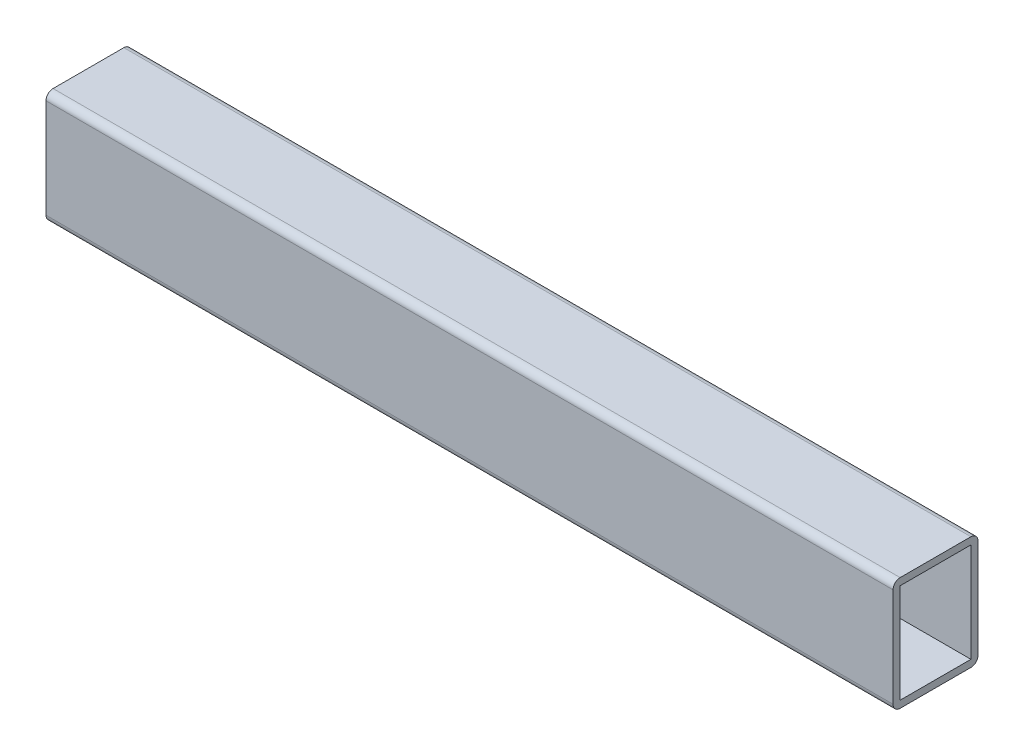
SolidWorks part; units mm, degrees
ref_plane "Front Plane" through (0, 0, 0) normal (0, 0, 1) x (1, 0, 0)
ref_plane "Top Plane" through (0, 0, 0) normal (0, 1, 0) x (1, 0, 0)
ref_plane "Right Plane" through (0, 0, 0) normal (1, 0, 0) x (0, 0, -1)
sketch "Sketch1" plane through (0, 0, 0) normal (1, 0, 0) x (0, 0, -1)
  line L0 (-19.05, 0) -> (19.05, 0) construction
  line L1 (-15.875, 25.4) -> (15.875, 25.4)
  line L2 (-19.05, 22.225) -> (-19.05, -22.225)
  line L3 (-15.875, -25.4) -> (15.875, -25.4)
  line L4 (19.05, 22.225) -> (19.05, -22.225)
  line L5 (0, 25.4) -> (0, -25.4) construction
  line L6 (-15.875, 22.225) -> (15.875, 22.225)
  line L7 (-15.875, 22.225) -> (-15.875, -22.225)
  line L8 (-15.875, -22.225) -> (15.875, -22.225)
  line L9 (15.875, 22.225) -> (15.875, -22.225)
  arc A0 (-15.875, 25.4) -> (-19.05, 22.225) centre (-15.875, 22.225) ccw
  arc A1 (19.05, 22.225) -> (15.875, 25.4) centre (15.875, 22.225) ccw
  arc A2 (-15.875, -25.4) -> (-19.05, -22.225) centre (-15.875, -22.225) cw
  arc A3 (15.875, -25.4) -> (19.05, -22.225) centre (15.875, -22.225) ccw
  point P10 (-19.05, 25.4)
  point P13 (19.05, 25.4)
  point P18 (19.05, -25.4)
  dimension "D3" = 3.175
  dimension "D1" = 50.8
  dimension "D2" = 38.1
  dimension "D4" = 3.175
  dimension "D5" = 3.175
extrude "Extrude1" add sketch "Sketch1" along normal blind 380
sketch "Mounting Holes" plane through (0, 0, 0) normal (0, -1, 0) x (1, 0, 0)
  line L0 (0, 0) -> (380, 0) construction
  line L1 (8.75, 10.05) -> (28.85, 10.05) construction
  line L2 (8.75, 10.05) -> (8.75, -10.05) construction
  line L3 (8.75, -10.05) -> (28.85, -10.05) construction
  line L4 (28.85, 10.05) -> (28.85, -10.05) construction
  line L5 (380, 15.875) -> (380, -15.875) construction
  line L6 (190, 19.05) -> (190, -19.05) construction
  line L7 (380, 19.05) -> (0, 19.05) construction
  line L8 (380, -19.05) -> (0, -19.05) construction
  line L9 (0, 15.875) -> (0, -15.875) construction
  line L10 (351.15, 10.05) -> (351.15, -10.05) construction
  line L11 (371.25, -10.05) -> (351.15, -10.05) construction
  line L12 (371.25, 10.05) -> (371.25, -10.05) construction
  line L13 (371.25, 10.05) -> (351.15, 10.05) construction
  circle A0 centre (8.75, 10.05) radius 2.1082
  circle A1 centre (28.85, 10.05) radius 2.1082
  circle A2 centre (28.85, -10.05) radius 2.1082
  circle A3 centre (8.75, -10.05) radius 2.1082
  circle A4 centre (351.15, 10.05) radius 2.1082
  circle A5 centre (371.25, 10.05) radius 2.1082
  circle A6 centre (371.25, -10.05) radius 2.1082
  circle A7 centre (351.15, -10.05) radius 2.1082
  dimension "D3" = 4.2164
  dimension "D1" = 9
  dimension "D2" = 8.75
sketch "Track" plane through (0, 0, 0) normal (0, 0, 1) x (1, 0, 0)
  line L0 (0, -11.96) -> (380, -11.96) construction
  line L1 (0, 22.225) -> (0, -22.225) construction
  line L2 (380, 22.225) -> (380, -22.225) construction
  line L3 (380, -25.4) -> (0, -25.4) construction
  line L4 (54, -3.96) -> (326, -3.96)
  line L5 (54, -3.96) -> (54, -19.96) construction
  line L6 (54, -19.96) -> (326, -19.96)
  line L7 (326, -3.96) -> (326, -19.96) construction
  arc A0 (54, -19.96) -> (54, -3.96) centre (54, -11.96) cw
  arc A1 (326, -19.96) -> (326, -3.96) centre (326, -11.96) ccw
  dimension "D1" = 16
  dimension "D2" = 54
  dimension "D3" = 326
  dimension "D4" = 13.44
sketch "Motor Mounts" plane through (0, 0, 0) normal (0, 0, 1) x (1, 0, 0)
  line L0 (0, -6.16) -> (380, -6.16) construction
  line L1 (0, 22.225) -> (0, -22.225) construction
  line L2 (380, 22.225) -> (380, -22.225) construction
  line L3 (380, -25.4) -> (0, -25.4) construction
  circle A0 centre (25, -6.16) radius 11.3109
  circle A1 centre (3.08, -6.16) radius 0.889
  circle A2 centre (25, 15.76) radius 0.889
  circle A3 centre (46.92, -6.16) radius 0.889
  circle A4 centre (25, -28.08) radius 0.889
  dimension "D2" = 22.6219
  dimension "D4" = 1.778
  dimension "D1" = 19.24
  dimension "D3" = 25
  dimension "D5" = 3.08
sketch "Access Port" plane through (0, 0, 0) normal (0, 0, 1) x (1, 0, 0)
  line L0 (253, 11.4) -> (253, -11.4)
  line L1 (380, 25.4) -> (0, 25.4) construction
  line L2 (380, -25.4) -> (0, -25.4) construction
  line L3 (380, 22.225) -> (380, -22.225) construction
  line L5 (261, -19.4) -> (350, -19.4)
  line L6 (358, 11.4) -> (358, -11.4)
  line L7 (261, 19.4) -> (350, 19.4)
  arc A0 (261, 19.4) -> (253, 11.4) centre (261, 11.4) ccw
  arc A1 (358, 11.4) -> (350, 19.4) centre (350, 11.4) ccw
  arc A2 (350, -19.4) -> (358, -11.4) centre (350, -11.4) ccw
  arc A3 (253, -11.4) -> (261, -19.4) centre (261, -11.4) ccw
  dimension "D2" = 8
  dimension "D3" = 6
  dimension "D4" = 22
  dimension "D5" = 105
  dimension "D1" = 6
sketch "Bushing Holes" plane through (0, 0, 0) normal (0, 0, 1) x (1, 0, 0)
  line L0 (0, -6.16) -> (380, -6.16) construction
  line L1 (380, 22.225) -> (380, -22.225) construction
  circle A0 centre (25, -6.16) radius 3
  circle A1 centre (370, -6.16) radius 3
  dimension "D1" = 6
  dimension "D2" = 10
sketch "Sketch7" plane through (0, 0, 0) normal (0, 1, 0) x (1, 0, 0)
  circle A0 centre (8.75, 10.05) radius 2.5527
  circle A1 centre (28.85, 10.05) radius 2.5527
  circle A2 centre (28.85, -10.05) radius 2.5527
  circle A3 centre (8.75, -10.05) radius 2.5527
  circle A4 centre (351.15, 10.05) radius 2.5527
  circle A5 centre (371.25, 10.05) radius 2.5527
  circle A6 centre (371.25, -10.05) radius 2.5527
  circle A7 centre (351.15, -10.05) radius 2.5527
  dimension "D1" = 5.1054
sketch "z mounting holes" plane through (0, 0, 0) normal (0, 0, 1) x (1, 0, 0)
  line L0 (0, 22.225) -> (0, -22.225) construction
  line L1 (60, 15.4) -> (240, 15.4) construction
  line L2 (60, 15.4) -> (60, -2.6) construction
  line L3 (60, -2.6) -> (240, -2.6) construction
  line L4 (240, 15.4) -> (240, -2.6) construction
  line L5 (380, -25.4) -> (0, -25.4) construction
  line L6 (380, 25.4) -> (0, 25.4) construction
  line L7 (96, 15.4) -> (96, -2.6) construction
  circle A0 centre (60, 15.4) radius 2.5
  circle A1 centre (240, 15.4) radius 2.5
  circle A2 centre (240, -2.6) radius 2.5
  circle A3 centre (60, -2.6) radius 2.5
  circle A4 centre (96, 15.4) radius 2.5
  circle A5 centre (96, -2.6) radius 2.5
  dimension "D1" = 5
  dimension "D2" = 180
  dimension "D3" = 60
  dimension "D4" = 22.8
  dimension "D5" = 18
  dimension "D6" = 10
  dimension "D7" = 36
